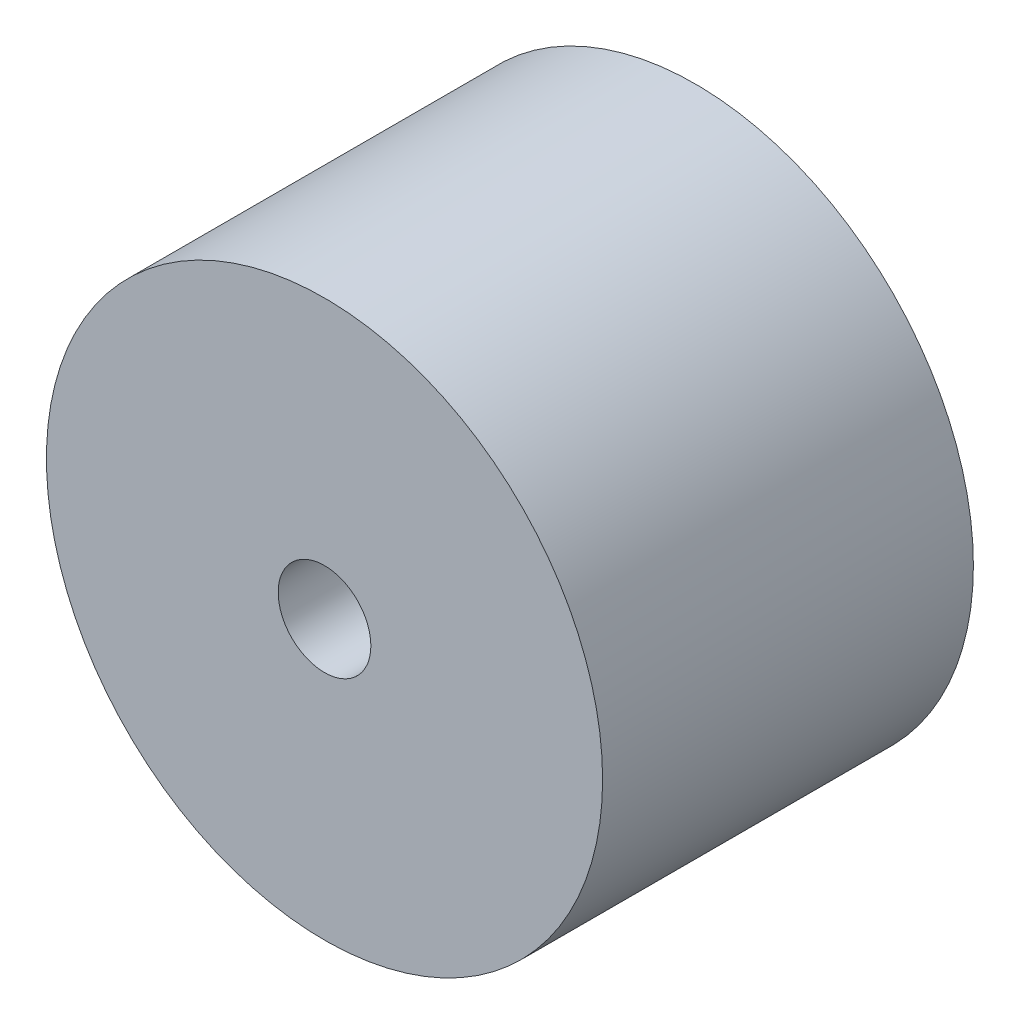
SolidWorks part; units mm, degrees
material "PET"
ref_plane "Front Plane" through (0, 0, 0) normal (0, 0, 1) x (1, 0, 0)
ref_plane "Top Plane" through (0, 0, 0) normal (0, 1, 0) x (1, 0, 0)
ref_plane "Right Plane" through (0, 0, 0) normal (1, 0, 0) x (0, 0, -1)
sketch "Sketch1" plane through (0, 0, 0) normal (0, 0, 1) x (1, 0, 0)
  circle A0 centre (0, 0) radius 5
  circle A1 centre (0, 0) radius 30
  dimension "D1" = 10
  dimension "D2" = 60
extrude "Boss-Extrude1" add sketch "Sketch1" along normal mid plane 40
